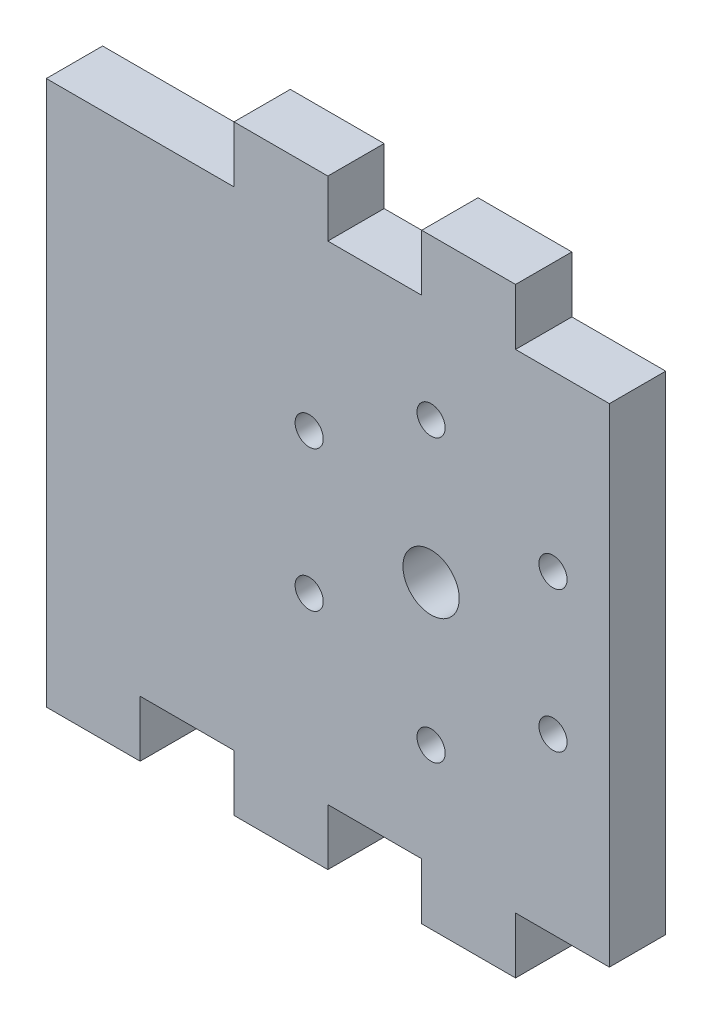
SolidWorks part; units mm, degrees
ref_plane "Alzado" through (0, 0, 0) normal (0, 0, 1) x (1, 0, 0)
ref_plane "Planta" through (0, 0, 0) normal (0, 1, 0) x (1, 0, 0)
ref_plane "Vista lateral" through (0, 0, 0) normal (1, 0, 0) x (0, 0, -1)
sketch "Sketch1" plane through (0, 0, 0) normal (0, 0, 1) x (1, 0, 0)
  line L0 (10, 0) -> (10, 3)
  line L1 (0, 0) -> (10, 0)
  line L2 (0, 0) -> (0, -29)
  line L3 (20.5, 0) -> (20.5, -26) construction
  line L4 (30, 0) -> (30, -26)
  line L5 (0, 0) -> (30, -26) construction
  line L6 (20.5, -13) -> (30, -13) construction
  line L7 (10, 3) -> (15, 3)
  line L8 (15, 3) -> (15, 0)
  line L9 (20, 0) -> (20, 3)
  line L10 (20, 3) -> (25, 3)
  line L11 (25, 3) -> (25, 0)
  line L12 (10, -26) -> (10, -29)
  line L13 (10, -29) -> (15, -29)
  line L14 (15, -29) -> (15, -26)
  line L15 (20, -29) -> (25, -29)
  line L16 (25, -29) -> (25, -26)
  line L17 (20, -29) -> (20, -26)
  line L18 (15, 0) -> (20, 0)
  line L19 (25, 0) -> (30, 0)
  line L20 (25, -26) -> (30, -26)
  line L21 (15, -26) -> (20, -26)
  line L23 (0, -29) -> (5, -29)
  line L24 (5, -29) -> (5, -26)
  line L25 (5, -26) -> (10, -26)
  circle A0 centre (20.5, -13) radius 7.5 construction
  circle A1 centre (20.5, -5.5) radius 0.75
  circle A2 centre (26.9952, -9.25) radius 0.75
  circle A3 centre (26.9952, -16.75) radius 0.75
  circle A4 centre (20.5, -20.5) radius 0.75
  circle A5 centre (14.0048, -16.75) radius 0.75
  circle A6 centre (14.0048, -9.25) radius 0.75
  circle A7 centre (20.5, -13) radius 1.5
  point P0 (0, 0)
  point P43 (20.5, -13)
  dimension "D7" = 15
  dimension "D8" = 1.5
  dimension "D10" = 3
  dimension "D1" = 30
  dimension "D2" = 5
  dimension "D3" = 3
  dimension "D4" = 29
  dimension "D5" = 3
  dimension "D6" = 9.5
  dimension "D9" = 6
extrude "Boss-Extrude1" add sketch "Sketch1" along normal blind 3
